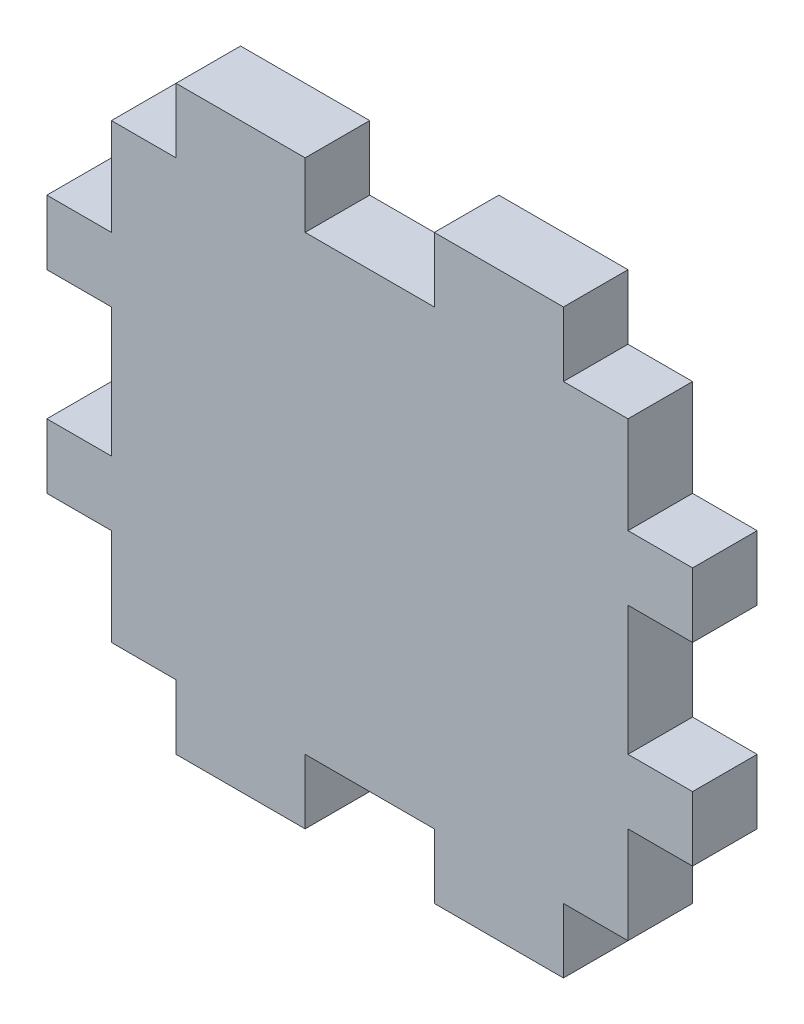
SolidWorks part; units mm, degrees
ref_plane "前视基准面" through (0, 0, 0) normal (0, 0, 1) x (1, 0, 0)
ref_plane "上视基准面" through (0, 0, 0) normal (0, 1, 0) x (1, 0, 0)
ref_plane "右视基准面" through (0, 0, 0) normal (1, 0, 0) x (0, 0, -1)
sketch "Model" plane through (0, 0, 0) normal (0, 0, 1) x (1, 0, 0)
  line L0 (1022.076, 566.4662) -> (1022.076, 569.4662)
  line L1 (1022.076, 569.4662) -> (1024.076, 569.4662)
  line L2 (1024.076, 569.4662) -> (1024.076, 571.4662)
  line L3 (1024.076, 571.4662) -> (1028.076, 571.4662)
  line L4 (1028.076, 571.4662) -> (1028.076, 569.4662)
  line L5 (1028.076, 569.4662) -> (1032.076, 569.4662)
  line L6 (1032.076, 569.4662) -> (1032.076, 571.4662)
  line L7 (1032.076, 571.4662) -> (1036.076, 571.4662)
  line L8 (1036.076, 571.4662) -> (1036.076, 569.4662)
  line L9 (1036.076, 569.4662) -> (1038.076, 569.4662)
  line L10 (1038.076, 569.4662) -> (1038.076, 566.4662)
  line L11 (1040.076, 566.4662) -> (1040.076, 564.4662)
  line L12 (1040.076, 564.4662) -> (1038.076, 564.4662)
  line L13 (1038.076, 564.4662) -> (1038.076, 560.4662)
  line L14 (1038.076, 560.4662) -> (1040.076, 560.4662)
  line L15 (1040.076, 560.4662) -> (1040.076, 558.4662)
  line L16 (1038.076, 555.4662) -> (1036.076, 555.4662)
  line L17 (1036.076, 555.4662) -> (1036.076, 553.4662)
  line L18 (1036.076, 553.4662) -> (1032.076, 553.4662)
  line L19 (1032.076, 553.4662) -> (1032.076, 555.4662)
  line L20 (1032.076, 555.4662) -> (1028.076, 555.4662)
  line L21 (1028.076, 555.4662) -> (1028.076, 553.4662)
  line L22 (1028.076, 553.4662) -> (1024.076, 553.4662)
  line L23 (1024.076, 553.4662) -> (1024.076, 555.4662)
  line L24 (1024.076, 555.4662) -> (1022.076, 555.4662)
  line L25 (1020.076, 558.4662) -> (1020.076, 560.4662)
  line L26 (1020.076, 560.4662) -> (1022.076, 560.4662)
  line L27 (1022.076, 560.4662) -> (1022.076, 564.4662)
  line L28 (1022.076, 564.4662) -> (1020.076, 564.4662)
  line L29 (1020.076, 564.4662) -> (1020.076, 566.4662)
  line L30 (1020.076, 566.4662) -> (1022.076, 566.4662)
  line L31 (1020.076, 558.4662) -> (1022.076, 558.4662)
  line L32 (1022.076, 558.4662) -> (1022.076, 555.4662)
  line L33 (1040.076, 566.4662) -> (1038.076, 566.4662)
  line L34 (1040.076, 558.4662) -> (1038.076, 558.4662)
  line L35 (1038.076, 558.4662) -> (1038.076, 555.4662)
extrude "凸台-拉伸1" add sketch "Model" along normal blind 2
